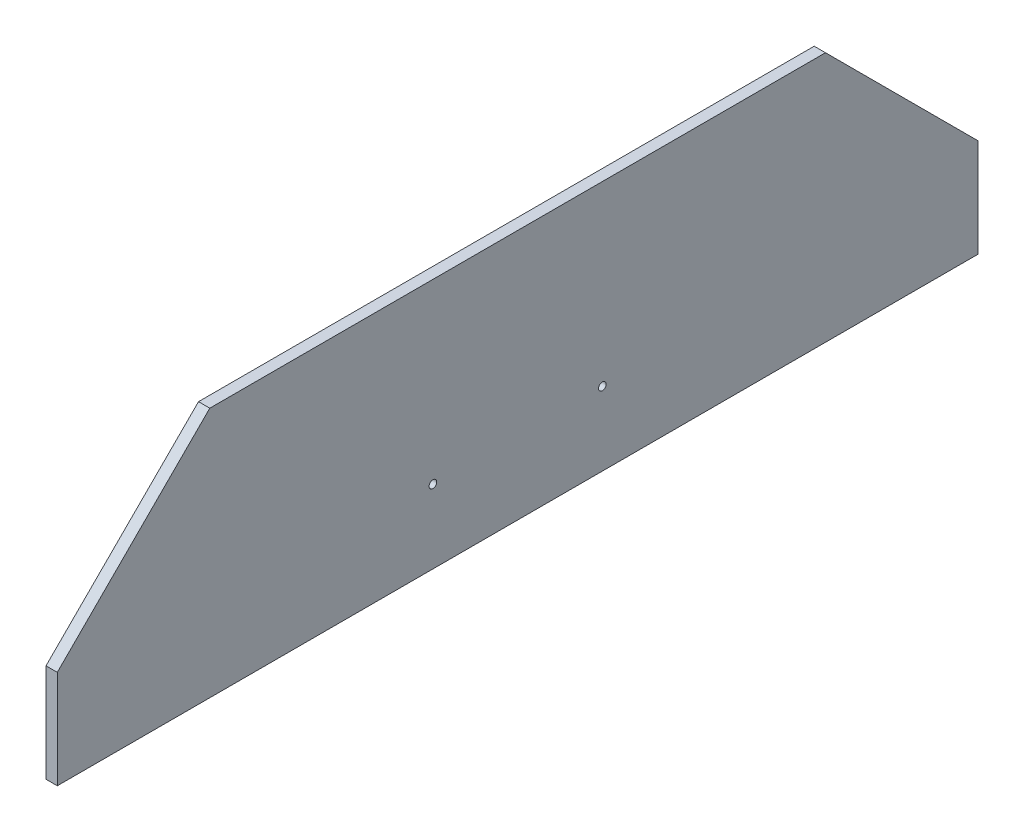
SolidWorks part; units mm, degrees
ref_plane "Front Plane" through (0, 0, 0) normal (0, 0, 1) x (1, 0, 0)
ref_plane "Top Plane" through (0, 0, 0) normal (0, 1, 0) x (1, 0, 0)
ref_plane "Right Plane" through (0, 0, 0) normal (1, 0, 0) x (0, 0, -1)
sketch "Sketch1" plane through (0, 0, 0) normal (1, 0, 0) x (0, 0, -1)
  line L1 (0, 0) -> (815, 0)
  line L2 (0, 0) -> (0, 222)
  line L3 (0, 222) -> (815, 222)
  line L4 (815, 0) -> (815, 222)
  dimension "D1" = 815
  dimension "D2" = 222
extrude "Boss-Extrude1" add sketch "Sketch1" along normal blind 10
chamfer "Chamfer1" distance 135 angle 45 2 edges at (5, 222, -815) (5, 222, 0)
hole_wizard "1/4 Clearance Hole1" positions "Sketch2" profile "Sketch3" hole size "1/4" standard "ANSI Inch" end condition through all
sketch "Sketch2" plane through (10, 0, 0) normal (1, 0, 0) x (0, 0, -1)
  line L0 (407.5, 0) -> (407.5, 222) construction
  line L1 (0, 0) -> (815, 0) construction
  line L2 (680, 222) -> (135, 222) construction
  point P0 (482.5, 65)
  point P13 (332.5, 65)
  dimension "D1" = 65
  dimension "D2" = 150
sketch "Sketch3" plane through (10, 65, -482.5) normal (0, 1, 0) x (0, 0, -1)
  line L0 (0, 0) -> (0, 10)
  line L1 (0, 10) -> (3.3782, 10)
  line L2 (3.3782, 10) -> (3.3782, 0)
  line L5 (3.3782, 0) -> (0, 0)
  line L11 (0, -6.35) -> (0, 107.95) construction
  dimension "Thru Hole Dia." = 6.7564
  dimension "Thru Hole Depth" = 10
